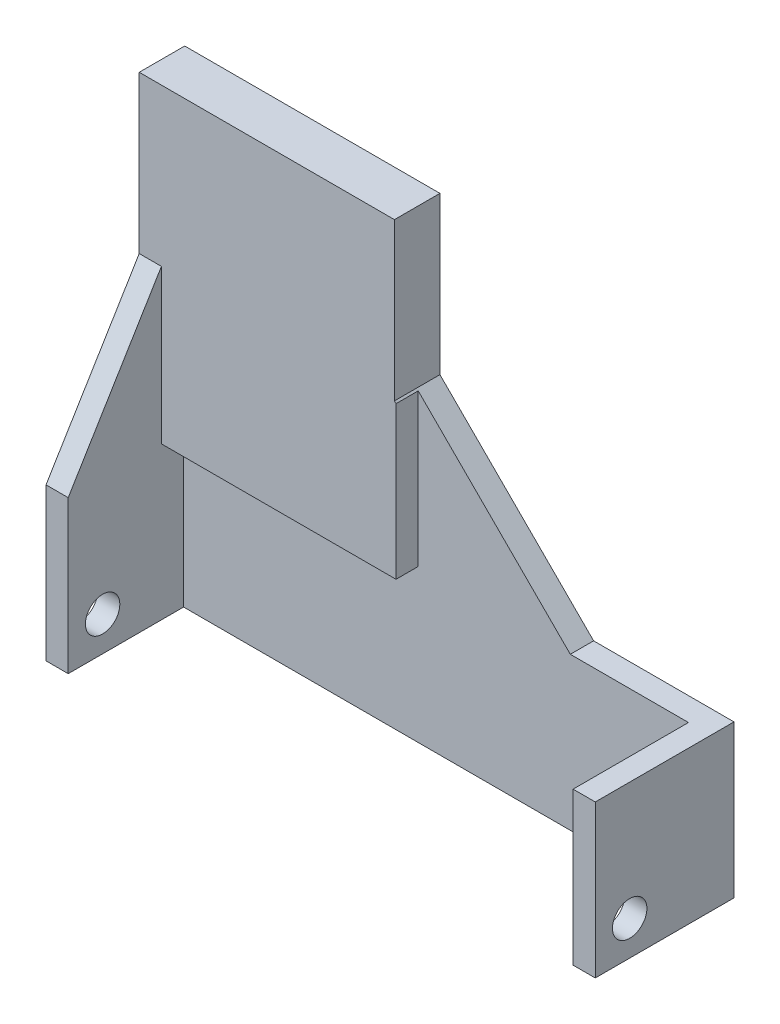
SolidWorks part; units mm, degrees
ref_plane "Front Plane" through (0, 0, 0) normal (0, 0, 1) x (1, 0, 0)
ref_plane "Top Plane" through (0, 0, 0) normal (0, 1, 0) x (1, 0, 0)
ref_plane "Right Plane" through (0, 0, 0) normal (1, 0, 0) x (0, 0, -1)
sketch "Sketch4" plane through (0, 0, 0) normal (0, 1, 0) x (1, 0, 0)
  line L0 (0, 0) -> (0, 8.4)
  line L1 (0, 8.4) -> (45.5, 8.4)
  line L2 (45.5, 8.4) -> (45.5, 0)
  line L3 (45.5, 0) -> (47.5, 0)
  line L4 (47.5, 0) -> (47.5, 12.5)
  line L5 (47.5, 12.5) -> (-2, 12.5)
  line L6 (-2, 12.5) -> (-2, 0)
  line L7 (-2, 0) -> (0, 0)
  dimension "D1" = 45.5
  dimension "D2" = 2
  dimension "D3" = 4.1
  dimension "D4" = 12.5
extrude "ProfileBoss-Extrude3" add sketch "Sketch4" along normal blind 41.74
sketch "Sketch5" plane through (47.5, 0, 0) normal (1, 0, 0) x (0, 0, -1)
  line L2 (0, 0) -> (12.5, 0) construction
  line L3 (0, 41.74) -> (0, 0) construction
  circle A0 centre (3.1, 3.1) radius 1.55
  dimension "D1" = 3.1
  dimension "D2" = 3.1
  dimension "D3" = 3.1
extrude "ShroudHolesCut-Extrude1" cut sketch "Sketch5" against normal through all
sketch "FrontCutoutSketch7" plane through (0, 0, -12.5) normal (0, 0, -1) x (-1, 0, 0)
  line L0 (-21, 41.74) -> (-21, 27.59)
  line L1 (-47.5, 41.74) -> (2, 41.74) construction
  line L2 (-21, 27.59) -> (-34.85, 13.74)
  line L3 (-34.85, 13.74) -> (-47.5, 13.74)
  line L4 (-47.5, 13.74) -> (-47.5, 41.74)
  line L5 (-47.5, 41.74) -> (-21, 41.74)
  line L6 (2, 41.74) -> (2, 0) construction
  dimension "D1" = 23
  dimension "D2" = 28
  dimension "D3" = 135
sketch "SideCutoutSketch9" plane through (-2, 0, 0) normal (-1, 0, 0) x (0, 0, 1)
  line L0 (0, 41.74) -> (-8.4, 41.74)
  line L1 (-12.5, 41.74) -> (0, 41.74) construction
  line L2 (-8.4, 41.74) -> (-8.4, 27.59)
  line L3 (-8.4, 27.59) -> (0, 13.74)
  line L4 (0, 41.74) -> (0, 0) construction
  line L5 (0, 13.74) -> (0, 41.74)
  line L7 (-8.4, 41.74) -> (-8.4, 0) construction
extrude "SideCutoutCut-Extrude3" cut sketch "SideCutoutSketch9" against normal through all
extrude "FrontCutoutCut-Extrude4" cut sketch "FrontCutoutSketch7" against normal through all
sketch "Sketch11" plane through (0, 0, -12.5) normal (0, 0, -1) x (-1, 0, 0)
  line L2 (-21, 41.59) -> (-21, 13.59) construction
  line L3 (-21, 41.74) -> (2, 41.74) construction
  line L10 (2, 41.74) -> (2, 0) construction
  circle A0 centre (-3, 21.74) radius 2.25
  circle A1 centre (-10.5, 27.74) radius 2.25
  circle A2 centre (-3, 33.74) radius 2.25
  point P17 (0, 13.59)
  point P18 (0, 0)
  point P19 (0, 27.59)
  point P20 (0, 0)
  point P21 (-48, 13.59)
  point P22 (-48, 0)
  point P23 (-48, 13.59)
  point P24 (-48, 0)
  point P25 (-50, 13.59)
  point P26 (-50, 0)
  point P27 (-50, 13.59)
  point P28 (-50, 0)
  dimension "D7" = 4.5
  dimension "D6" = 10.5
  dimension "D1" = 12
  dimension "D2" = 6
  dimension "D3" = 7.5
  dimension "D4" = 5
  dimension "D5" = 8
extrude "DragChainMountHolesCut-Extrude6" cut sketch "Sketch11" against normal blind 3.1
sketch "Sketch13" plane through (0, 0, -8.4) normal (0, 0, 1) x (1, 0, 0)
  line L0 (21.1427, 27.4473) -> (34.85, 13.74)
  line L1 (34.85, 13.74) -> (21, 27.59) construction
  line L2 (34.85, 13.74) -> (45.5, 13.74)
  line L3 (45.5, 13.74) -> (45.5, 0) construction
  line L4 (45.5, 13.74) -> (45.5, 0)
  line L5 (45.5, 0) -> (0, 0)
  line L6 (0, 0) -> (0, 13.74)
  line L7 (0, 13.74) -> (21.1427, 13.74)
  line L8 (21.1427, 13.74) -> (21.1427, 27.4473)
  line L9 (45.5, 13.74) -> (34.85, 13.74) construction
  line L10 (21, 27.59) -> (21, 41.74) construction
  dimension "D1" = 0.1427
extrude "Cut-Extrude7" cut sketch "Sketch13" against normal blind 2
equation "\"HotEndShourdWidth\"=46.1"
equation "\"HotEndShroudHeight\"= \"DragChainHeight\" + \"ShroudHeightBelowDragChainToMountHole\" + \"HotEndShroudMountingoleDiameter\" * 1.5"
equation "\"D1@ProfileBoss-Extrude3\" = \"HotEndShroudHeight\""
equation "\"DragChainHeight\"= 28mm"
equation "\"ShroudHeightBelowDragChainToMountHole\"= 9.09mm'Measured"
equation "\"HotEndShroudMountingoleDiameter\"= \"M3ScrewDiameter\" + .1mm'Add .1 for printing"
equation "\"D2@Sketch5\"=\"HotEndShroudMountingoleDiameter\""
equation "\"D3@Sketch5\"=\"HotEndShroudMountingoleDiameter\""
equation "\"D1@Sketch5\"=\"HotEndShroudMountingoleDiameter\""
equation "\"D5@Sketch11\"=(\"DragChainHeight\" -12)/2"
equation "\"M3ScrewDiameter\"= 3mm"
